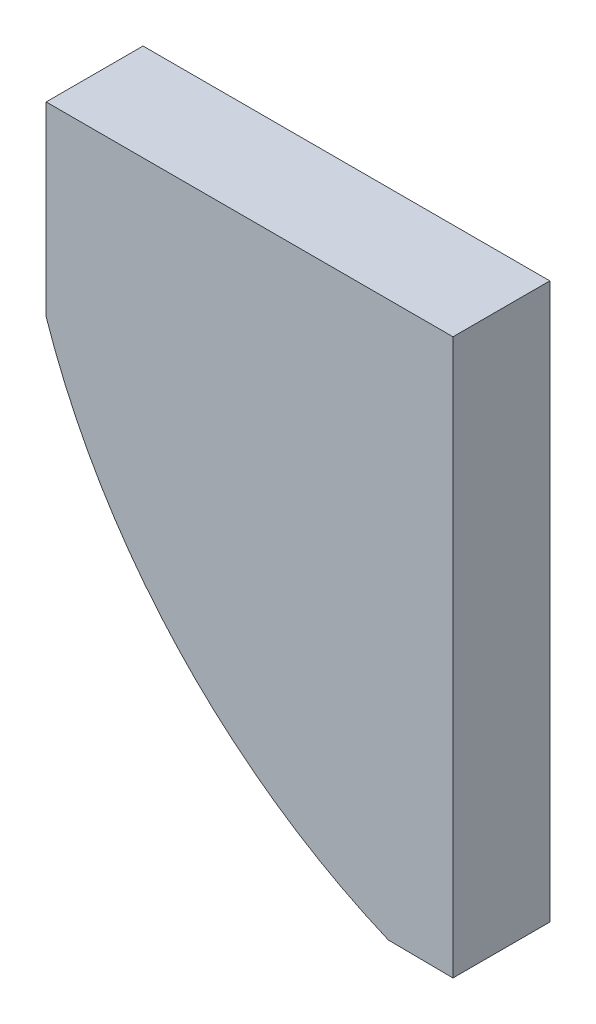
SolidWorks part; units mm, degrees
ref_plane "Front Plane" through (0, 0, 0) normal (0, 0, 1) x (1, 0, 0)
ref_plane "Top Plane" through (0, 0, 0) normal (0, 1, 0) x (1, 0, 0)
ref_plane "Right Plane" through (0, 0, 0) normal (1, 0, 0) x (0, 0, -1)
sketch "Sketch1" plane through (0, 0, 0) normal (0, 0, 1) x (1, 0, 0)
  line L0 (-97.9242, -245.6087) -> (-107.9242, -245.5211)
  line L1 (-97.9242, -245.6087) -> (-97.9242, -159.6087)
  line L2 (-97.9242, -159.6087) -> (-160.9242, -159.6087)
  line L3 (-160.9242, -159.6087) -> (-160.9242, -188.4363)
  arc A0 (-160.9242, -188.4363) -> (-107.9242, -245.5211) centre (-70.9242, -158.0225) ccw
  point P7 (0, 0)
  point P9 (0, 0)
  point P12 (0, 0)
  point P13 (0, 0)
extrude "Boss-Extrude1" add sketch "Sketch1" along normal blind 15 contours A0 L0 L1 L2 L3
shell "Shell1" thickness 5
